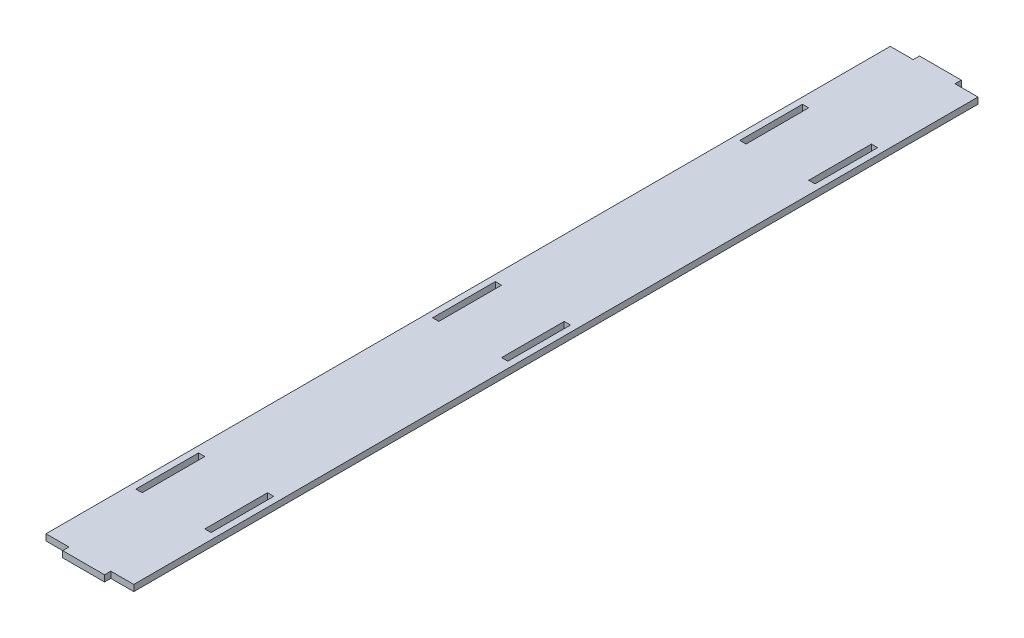
SolidWorks part; units mm, degrees
material "ABS"
ref_plane "Front Plane" through (0, 0, 0) normal (0, 0, 1) x (1, 0, 0)
ref_plane "Top Plane" through (0, 0, 0) normal (0, 1, 0) x (1, 0, 0)
ref_plane "Right Plane" through (0, 0, 0) normal (1, 0, 0) x (0, 0, -1)
sketch "Sketch1" plane through (0, 0, 0) normal (0, 1, 0) x (1, 0, 0)
  line L0 (31, 0) -> (42, 0)
  line L1 (0, 0) -> (11, 0)
  line L2 (0, 0) -> (0, 404)
  line L3 (0, 404) -> (11, 404)
  line L4 (42, 0) -> (42, 404)
  line L6 (11, 404) -> (11, 407)
  line L7 (11, 407) -> (31, 407)
  line L8 (31, 404) -> (31, 407)
  line L10 (11, 0) -> (11, -3)
  line L11 (11, -3) -> (31, -3)
  line L12 (31, 0) -> (31, -3)
  line L13 (36, 359) -> (39, 359)
  line L14 (36, 359) -> (36, 329)
  line L15 (36, 329) -> (39, 329)
  line L16 (39, 359) -> (39, 329)
  line L17 (36, 212) -> (39, 212)
  line L18 (36, 212) -> (36, 182)
  line L19 (36, 182) -> (39, 182)
  line L20 (39, 212) -> (39, 182)
  line L25 (36, 70) -> (39, 70)
  line L26 (36, 70) -> (36, 40)
  line L27 (36, 40) -> (39, 40)
  line L28 (39, 70) -> (39, 40)
  line L29 (21, -3) -> (21, 275.749) construction
  line L30 (31, 404) -> (42, 404)
  line L31 (11, 404) -> (0, 404)
  line L32 (3, 70) -> (3, 40)
  line L33 (6, 40) -> (3, 40)
  line L34 (6, 70) -> (6, 40)
  line L35 (6, 70) -> (3, 70)
  line L36 (3, 212) -> (3, 182)
  line L37 (6, 182) -> (3, 182)
  line L38 (6, 212) -> (6, 182)
  line L39 (6, 212) -> (3, 212)
  line L40 (3, 359) -> (3, 329)
  line L41 (6, 329) -> (3, 329)
  line L42 (6, 359) -> (6, 329)
  line L43 (6, 359) -> (3, 359)
  line L44 (11, 404) -> (11, 407)
  line L45 (31, 404) -> (31, 407)
  line L46 (42, 404) -> (31, 404)
  dimension "D1" = 404
  dimension "D2" = 42
  dimension "D3" = 20
  dimension "D4" = 3
  dimension "D6" = 20
  dimension "D7" = 3
  dimension "D8" = 11
  dimension "D9" = 30
  dimension "D10" = 3
  dimension "D11" = 3
  dimension "D12" = 40
  dimension "D13" = 3
  dimension "D14" = 30
  dimension "D15" = 3
  dimension "D16" = 112
  dimension "D17" = 30
  dimension "D18" = 3
  dimension "D19" = 3
  dimension "D20" = 117
extrude "Boss-Extrude1" add sketch "Sketch1" along normal blind 3
